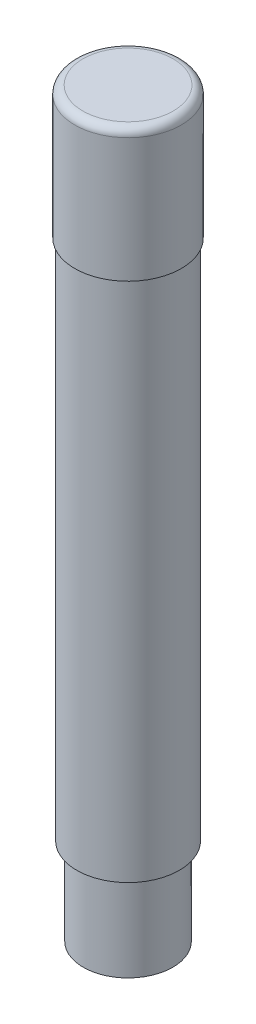
SolidWorks part; units mm, degrees
ref_plane "Front Plane" through (0, 0, 0) normal (0, 0, 1) x (1, 0, 0)
ref_plane "Top Plane" through (0, 0, 0) normal (0, 1, 0) x (1, 0, 0)
ref_plane "Right Plane" through (0, 0, 0) normal (1, 0, 0) x (0, 0, -1)
sketch "Sketch2" plane through (0, 0, 0) normal (0, 0, 1) x (1, 0, 0)
  line L0 (0, 0) -> (0, 91.9)
  line L1 (0, 91.9) -> (-6.6, 91.9)
  line L2 (-6.6, 91.9) -> (-6.6, 75.5)
  line L3 (-6.6, 75.5) -> (-6.35, 75.5)
  line L4 (-6.35, 75.5) -> (-6.35, 10.8)
  line L5 (-6.35, 10.8) -> (-5.55, 10.8)
  line L6 (-5.55, 10.8) -> (-5.55, 0)
  line L7 (-5.55, 0) -> (0, 0)
  dimension "D1" = 16.4
  dimension "D2" = 81.1
  dimension "D3" = 91.9
  dimension "D4" = 6.35
  dimension "D5" = 6.6
  dimension "D6" = 5.55
revolve "Revolve1" add sketch "Sketch2" angle 360 about L0
fillet "Fillet1" radius 1 1 edges at (0, 91.9, -6.6)
equation "\"D5@Sketch2\"=13.2/2"
equation "\"D4@Sketch2\"=12.7/2"
equation "\"D6@Sketch2\"=11.1/2"
